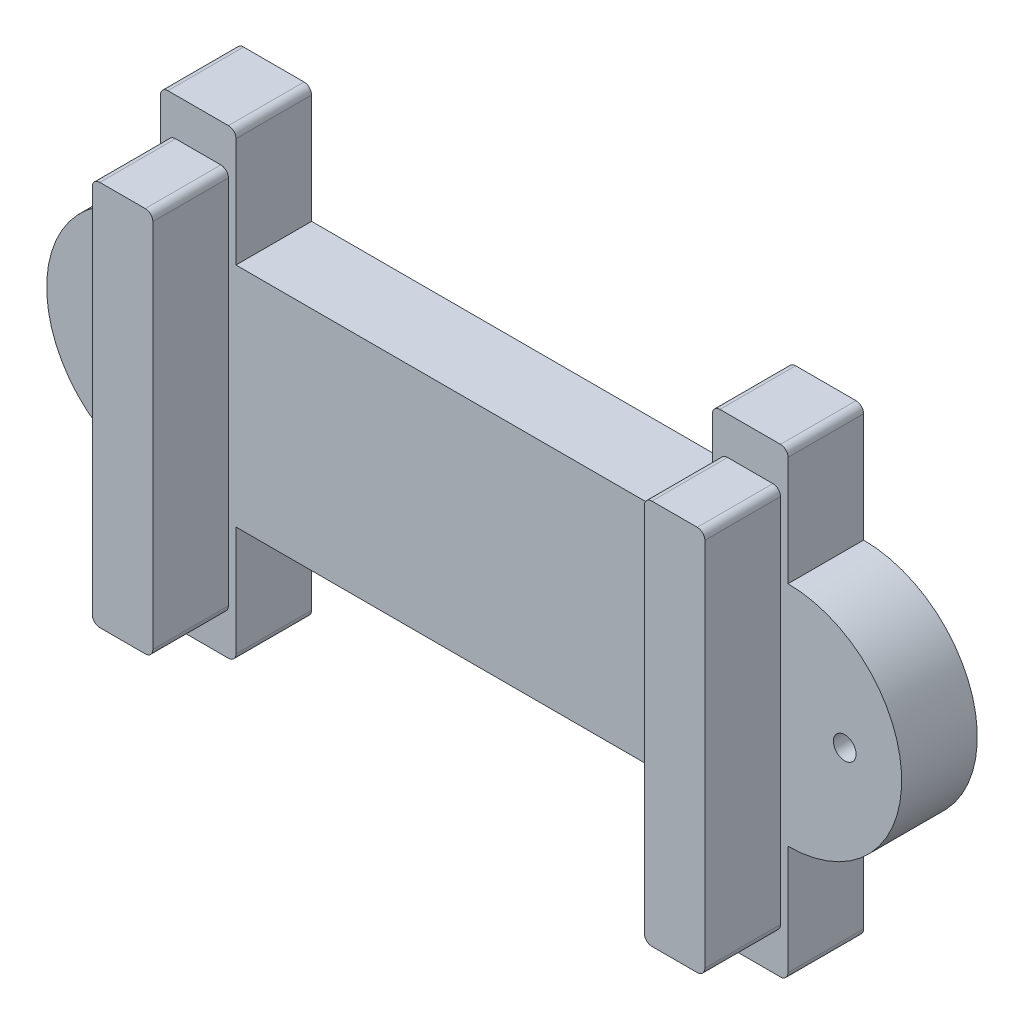
SolidWorks part; units mm, degrees
ref_plane "Front Plane" through (0, 0, 0) normal (0, 0, 1) x (1, 0, 0)
ref_plane "Top Plane" through (0, 0, 0) normal (0, 1, 0) x (1, 0, 0)
ref_plane "Right Plane" through (0, 0, 0) normal (1, 0, 0) x (0, 0, -1)
sketch "Sketch1" plane through (0, 0, 0) normal (0, 0, 1) x (1, 0, 0)
  line L0 (0, 20.4922) -> (0, 15) construction
  line L1 (31.5, -15) -> (-31.5, -15)
  line L3 (31.5, 15) -> (-31.5, 15)
  line L5 (40.5, 30.4662) -> (32.5, 30.4662)
  line L6 (-40.5, -30.5338) -> (-32.5, -30.5338)
  line L7 (-41.5, -29.5338) -> (-41.5, -15.0677)
  line L8 (-40.5, 30.4662) -> (-32.5, 30.4662)
  line L9 (-31.5, -29.5338) -> (-31.5, -15)
  line L10 (-41.5, -30.5338) -> (-41.4056, -29.958) construction
  line L11 (-41.5, 30.4662) -> (-41.4056, 29.8903) construction
  line L12 (31.5, -29.5338) -> (31.5, -15)
  line L13 (40.5, -30.5338) -> (32.5, -30.5338)
  line L14 (41.5, -29.5338) -> (41.5, -15.0677)
  line L16 (-31.5, 15) -> (-31.5, 29.4662)
  line L17 (-31.5944, 29.8903) -> (-31.5, 30.4662) construction
  line L18 (-36.5055, 0) -> (-36.5, -0.0338) construction
  line L19 (-41.5, 15) -> (-41.5, 29.4662)
  line L20 (-36.5055, 0) -> (-36.4945, 0) construction
  line L21 (-36.5, -0.0338) -> (-36.4945, 0) construction
  line L22 (-31.5944, -29.958) -> (-31.5, -30.5338) construction
  line L24 (0, -15) -> (0, -24.7233) construction
  line L25 (31.5, 15) -> (31.5, 29.4662)
  line L26 (41.5, 15) -> (41.5, 29.4662)
  arc A0 (-41.5, 29.4662) -> (-40.5, 30.4662) centre (-40.5, 29.4662) cw
  arc A1 (-31.5, 29.4662) -> (-32.5, 30.4662) centre (-32.5, 29.4662) ccw
  arc A4 (-32.5, -30.5338) -> (-31.5, -29.5338) centre (-32.5, -29.5338) ccw
  arc A5 (-40.5, -30.5338) -> (-41.5, -29.5338) centre (-40.5, -29.5338) cw
  arc A6 (32.5, -30.5338) -> (31.5, -29.5338) centre (32.5, -29.5338) cw
  arc A7 (40.5, -30.5338) -> (41.5, -29.5338) centre (40.5, -29.5338) ccw
  arc A8 (41.5, 29.4662) -> (40.5, 30.4662) centre (40.5, 29.4662) ccw
  arc A9 (31.5, 29.4662) -> (32.5, 30.4662) centre (32.5, 29.4662) cw
  arc A10 (-41.5, 15) -> (-41.5, -15.0677) centre (-41.5, -0.0338) ccw
  arc A11 (41.5, 15) -> (41.5, -15.0677) centre (41.5, -0.0338) cw
  circle A12 centre (-49, -0.0338) radius 1.5
  circle A13 centre (49, -0.0338) radius 1.5
  point P0 (0, 0)
  point P30 (31.5, -30.5338)
  point P33 (41.5, -30.5338)
  point P36 (41.5, 30.4662)
  point P39 (31.5, 30.4662)
  dimension "D3" = 10
  dimension "D5" = 1
  dimension "D6" = 7.5
  dimension "D1" = 63
  dimension "D2" = 30
  dimension "D4" = 61
extrude "Boss-Extrude1" add sketch "Sketch1" along normal blind 10
sketch "Sketch2" plane through (0, 0, 10) normal (0, 0, 1) x (1, 0, 0)
  line L0 (0, 26.5444) -> (0, -31.0619) construction
  line L1 (-33.5, -25.5338) -> (-39.5, -25.5338)
  line L2 (-32.5, -24.5338) -> (-32.5, 24.4662)
  line L3 (-33.5, 25.4662) -> (-39.5, 25.4662)
  line L4 (-40.5, -24.5338) -> (-40.5, 24.4662)
  line L5 (-32.5, -25.5338) -> (-40.5, 25.4662) construction
  line L6 (-32.5, 25.4662) -> (-40.5, -25.5338) construction
  line L7 (33.5, 25.4662) -> (39.5, 25.4662)
  line L8 (40.5, -24.5338) -> (40.5, 24.4662)
  line L9 (33.5, -25.5338) -> (39.5, -25.5338)
  line L10 (32.5, -24.5338) -> (32.5, 24.4662)
  line L11 (-32.5, 30.4662) -> (-40.5, 30.4662) construction
  line L12 (-49, -0.0338) -> (29.7653, -0.0338) construction
  arc A0 (40.5, -24.5338) -> (39.5, -25.5338) centre (39.5, -24.5338) cw
  arc A1 (33.5, -25.5338) -> (32.5, -24.5338) centre (33.5, -24.5338) cw
  arc A2 (40.5, 24.4662) -> (39.5, 25.4662) centre (39.5, 24.4662) ccw
  arc A3 (32.5, 24.4662) -> (33.5, 25.4662) centre (33.5, 24.4662) cw
  arc A4 (-32.5, 24.4662) -> (-33.5, 25.4662) centre (-33.5, 24.4662) ccw
  arc A5 (-33.5, -25.5338) -> (-32.5, -24.5338) centre (-33.5, -24.5338) ccw
  arc A6 (-39.5, -25.5338) -> (-40.5, -24.5338) centre (-39.5, -24.5338) cw
  arc A7 (-40.5, 24.4662) -> (-39.5, 25.4662) centre (-39.5, 24.4662) cw
  point P0 (-36.5, -0.0338)
  point P20 (40.5, -25.5338)
  point P23 (32.5, -25.5338)
  point P26 (40.5, 25.4662)
  point P29 (32.5, 25.4662)
  dimension "D4" = 1
  dimension "D1" = 36.5
  dimension "D2" = 8
  dimension "D3" = 5
extrude "Boss-Extrude2" add sketch "Sketch2" along normal blind 10
